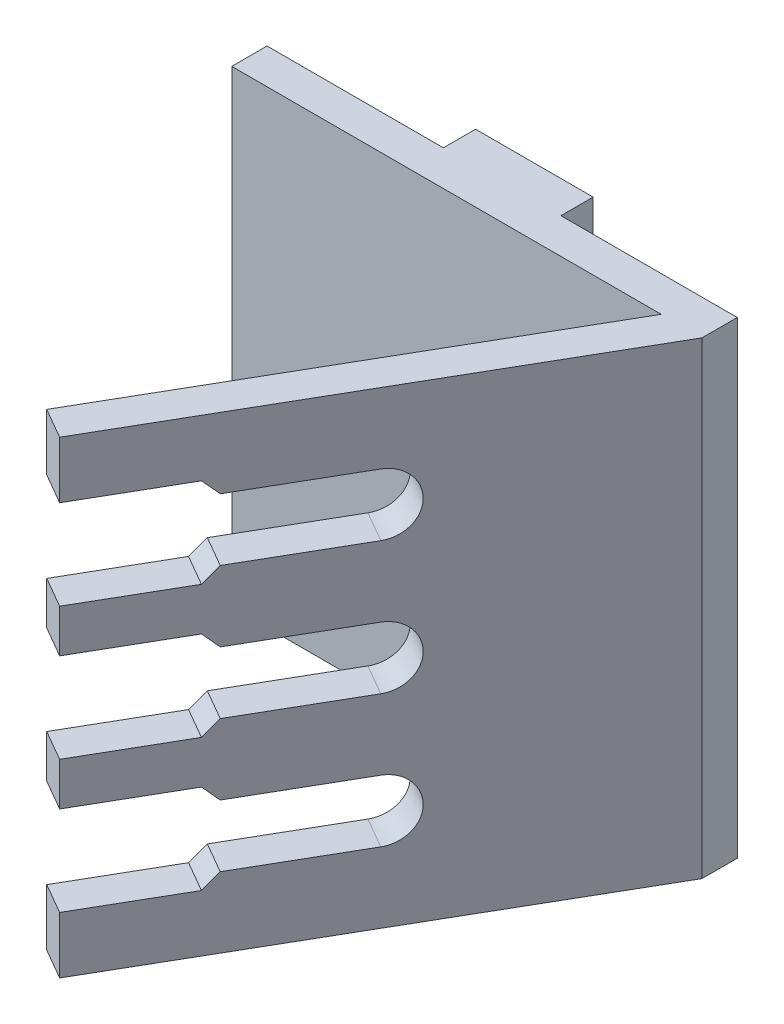
SolidWorks part; units mm, degrees
ref_plane "Front Plane" through (0, 0, 0) normal (1, 0, 0) x (0, 1, 0)
ref_plane "Top Plane" through (0, 0, 0) normal (0, 0, 1) x (0, 1, 0)
ref_plane "Right Plane" through (0, 0, 0) normal (0, 1, 0) x (-1, 0, 0)
sketch "Sketch1" plane through (0, 0, 0) normal (0, 1, 0) x (-1, 0, 0)
  line L0 (-12.0039, -2.8355) -> (-12.0039, -5.8355)
  line L1 (-12.0039, -5.8355) -> (27.9961, -5.8355)
  line L2 (27.9961, -5.8355) -> (27.9961, -2.8355)
  line L3 (27.9961, -2.8355) -> (-8.5398, -2.8355)
  line L4 (-8.5398, -2.8355) -> (10.5942, 30.3055)
  line L5 (10.5942, 30.3055) -> (7.9961, 31.8055)
  line L6 (7.9961, 31.8055) -> (-12.0039, -2.8355)
  dimension "D1" = 3
  dimension "D2" = 3
  dimension "D3" = 40
  dimension "D4" = 40
  dimension "D5" = 60
extrude "Boss-Extrude1" add sketch "Sketch1" along normal blind 39.84
sketch "Sketch2" plane through (7.7751, 0, 4.489) normal (0.866, 0, 0.5) x (0, 1, 0)
  line L0 (6, 21.5424) -> (6, 11.5424)
  line L1 (39.84, 31.5424) -> (0, 31.5424) construction
  line L2 (11.28, 21.5424) -> (11.28, 11.5424)
  line L3 (0, 31.5424) -> (0, -8.4576) construction
  line L4 (6, 31.5424) -> (11.28, 31.5424)
  line L11 (6, 21.5424) -> (4.83, 22.7124)
  line L12 (4.83, 22.7124) -> (4.83, 31.5424)
  line L13 (4.83, 31.5424) -> (6, 31.5424)
  line L14 (11.28, 21.5424) -> (12.45, 22.7124)
  line L15 (12.45, 22.7124) -> (12.45, 31.5424)
  line L16 (12.45, 31.5424) -> (11.28, 31.5424)
  line L17 (22.56, 21.5424) -> (22.56, 11.5424)
  line L18 (17.28, 21.5424) -> (17.28, 11.5424)
  line L19 (17.28, 21.5424) -> (16.11, 22.7124)
  line L20 (16.11, 22.7124) -> (16.11, 31.5424)
  line L21 (16.11, 31.5424) -> (17.28, 31.5424)
  line L22 (17.28, 31.5424) -> (22.56, 31.5424)
  line L23 (23.73, 31.5424) -> (22.56, 31.5424)
  line L24 (23.73, 22.7124) -> (23.73, 31.5424)
  line L25 (22.56, 21.5424) -> (23.73, 22.7124)
  line L26 (33.84, 21.5424) -> (33.84, 11.5424)
  line L27 (28.56, 21.5424) -> (28.56, 11.5424)
  line L28 (28.56, 21.5424) -> (27.39, 22.7124)
  line L29 (27.39, 22.7124) -> (27.39, 31.5424)
  line L30 (27.39, 31.5424) -> (28.56, 31.5424)
  line L31 (28.56, 31.5424) -> (33.84, 31.5424)
  line L32 (35.01, 31.5424) -> (33.84, 31.5424)
  line L33 (35.01, 22.7124) -> (35.01, 31.5424)
  line L34 (33.84, 21.5424) -> (35.01, 22.7124)
  arc A0 (11.28, 11.5424) -> (6, 11.5424) centre (8.64, 11.5424) cw
  arc A3 (22.56, 11.5424) -> (17.28, 11.5424) centre (19.92, 11.5424) cw
  arc A4 (33.84, 11.5424) -> (28.56, 11.5424) centre (31.2, 11.5424) cw
  dimension "D1" = 5.28
  dimension "D2" = 20
  dimension "D3" = 6
  dimension "D6" = 7.62
  dimension "D7" = 135
  dimension "D8" = 135
  dimension "D9" = 10
  dimension "D5" = 6
  dimension "D4" = 3
extrude "Cut-Extrude1" cut sketch "Sketch2" against normal up to next
sketch "Sketch3" plane through (0, 0, -5.8355) normal (0, 0, -1) x (1, 0, 0)
  line L0 (12.0039, 0) -> (-27.9961, 0) construction
  line L1 (-2.9961, 0) -> (-12.9961, 0)
  line L2 (-2.9961, 0) -> (-2.9961, -2.74)
  line L3 (-2.9961, -2.74) -> (-12.9961, -2.74)
  line L4 (-12.9961, 0) -> (-12.9961, -2.74)
  line L5 (12.0039, -19.92) -> (-27.9961, -19.92) construction
  line L6 (12.0039, -39.84) -> (12.0039, 0) construction
  line L7 (-27.9961, -39.84) -> (-27.9961, 0) construction
  line L8 (-2.9961, -37.1) -> (-12.9961, -37.1)
  line L9 (-12.9961, -39.84) -> (-12.9961, -37.1)
  line L10 (-2.9961, -39.84) -> (-12.9961, -39.84)
  line L11 (-2.9961, -39.84) -> (-2.9961, -37.1)
  point P6 (-7.9961, 0)
  point P7 (-7.9961, 0)
  dimension "D1" = 10
  dimension "D2" = 2.74
extrude "Boss-Extrude2" add sketch "Sketch3" along normal blind 2.74
equation "\"cable width\"= .2in"
equation "\"clearance\"= 0.2mm"
equation "\"slot_width\"= \"cable width\" + \"clearance\""
equation "\"base\"= ( \"slot_width\" ) * 3 + 4 * ( 6 )"
equation "\"depth\" = 40mm"
equation "\"thick\"= 3mm"
equation "\"D1@Sketch1\"=\"thick\""
equation "\"D2@Sketch1\"=\"thick\""
equation "\"D3@Sketch1\"=\"depth\""
equation "\"D4@Sketch1\"=\"depth\""
equation "\"D1@Boss-Extrude1\"=\"base\""
equation "\"D1@Sketch2\"=\"slot_width\""
equation "\"D2@Sketch2\"=\"depth\"*(1/2)"
equation "\"avg_t_wood\"= 2.74mm"
equation "\"ideal_t_wood\"= 3mm"
equation "\"kerf\"= 0.2mm"
equation "\"slot_height\"= \"avg_t_wood\" + \"kerf\""
equation "\"wood_slot_width\"= 10mm + \"kerf\""
equation "\"wood_slot_clearance\"= - .2mm"
equation "\"woodstand_width\"= 10mm"
equation "\"woodstand_length\" = 75mm"
equation "\"D2@Sketch3\"=\"slot_height\"-\"kerf\""
equation "\"D1@Boss-Extrude2\"=\"avg_t_wood\""
equation "\"D1@Sketch3\"=\"wood_slot_width\"-\"kerf\""
equation "\"D6@Sketch2\"=\"cable width\"+\"cable width\"*.5"
equation "\"D9@Sketch2\"=\"depth\"*(1/4)"
